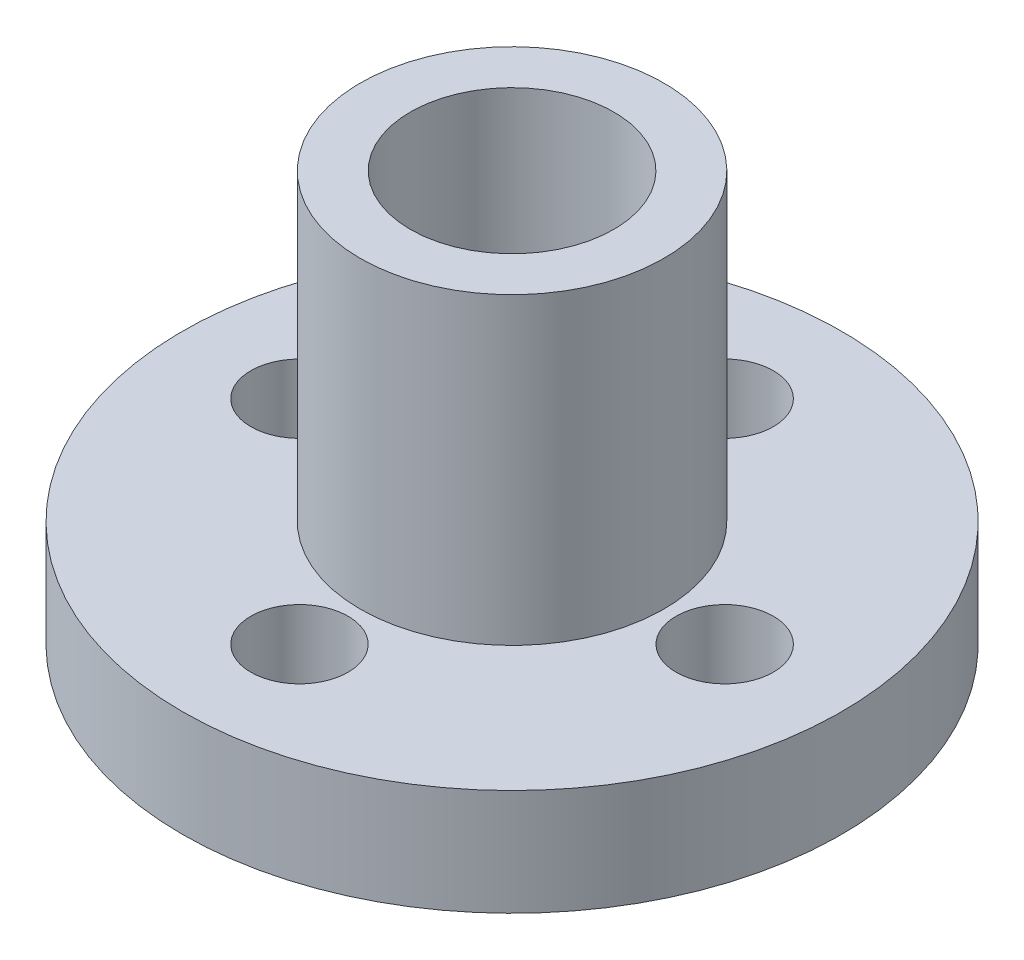
SolidWorks part; units mm, degrees
ref_plane "Спереди" through (0, 0, 0) normal (0, 0, 1) x (1, 0, 0)
ref_plane "Сверху" through (0, 0, 0) normal (0, 1, 0) x (1, 0, 0)
ref_plane "Справа" through (0, 0, 0) normal (1, 0, 0) x (0, 0, -1)
sketch "Эскиз1" plane through (0, 0, 0) normal (0, 1, 0) x (1, 0, 0)
  circle A0 centre (0, 0) radius 10.85
  circle A1 centre (0, 0) radius 3.4
extrude "Бобышка-Вытянуть1" add sketch "Эскиз1" along normal blind 3.5
sketch "Эскиз2" plane through (0, 3.5, 0) normal (0, 1, 0) x (1, 0, 0)
  circle A0 centre (0, 0) radius 5
  circle A1 centre (0, 0) radius 3.35
extrude "Бобышка-Вытянуть2" add sketch "Эскиз2" along normal blind 10
sketch "Эскиз3" plane through (0, 3.5, 0) normal (0, 1, 0) x (1, 0, 0)
  circle A0 centre (0, 0) radius 7 construction
  circle A2 centre (0, 7) radius 1.6
  circle A3 centre (-7, 0) radius 1.6
  circle A4 centre (0, -7) radius 1.6
  circle A5 centre (7, 0) radius 1.6
extrude "Вырез-Вытянуть1" cut sketch "Эскиз3" against normal through all
sketch "Эскиз4" plane through (0, 0, 0) normal (0, -1, 0) x (-1, 0, 0)
  circle A0 centre (0, 0) radius 5
  circle A1 centre (0, 0) radius 3.35
extrude "Бобышка-Вытянуть3" add sketch "Эскиз4" along normal blind 1.5
